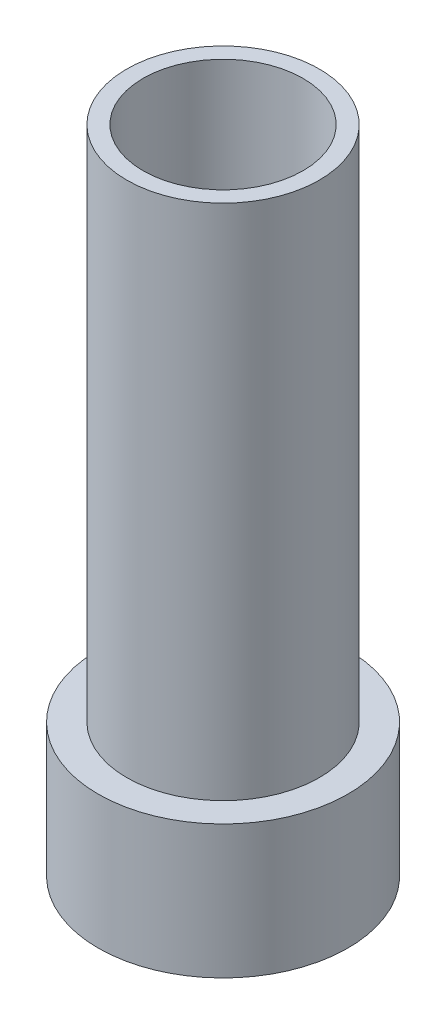
SolidWorks part; units mm, degrees
material "PP Film"
ref_plane "Front Plane" through (0, 0, 0) normal (0, 0, 1) x (1, 0, 0)
ref_plane "Top Plane" through (0, 0, 0) normal (0, 1, 0) x (1, 0, 0)
ref_plane "Right Plane" through (0, 0, 0) normal (1, 0, 0) x (0, 0, -1)
sketch "Sketch1" plane through (0, 0, 0) normal (0, 1, 0) x (1, 0, 0)
  circle A0 centre (0, 0) radius 4.68
  dimension "D1" = 9.36
extrude "Boss-Extrude1" add sketch "Sketch1" along normal blind 5
sketch "Sketch2" plane through (0, 5, 0) normal (0, 1, 0) x (1, 0, 0)
  circle A0 centre (0, 0) radius 3.61
  circle A1 centre (0, 0) radius 3
  dimension "D1" = 6
  dimension "D2" = 7.22
extrude "Boss-Extrude2" add sketch "Sketch2" along normal blind 19.4
sketch "Sketch3" plane through (0, 5, 0) normal (0, 1, 0) x (1, 0, 0)
  circle A0 centre (0, 0) radius 3
extrude "Boss-Extrude4" add sketch "Sketch3" along normal blind 14.05
